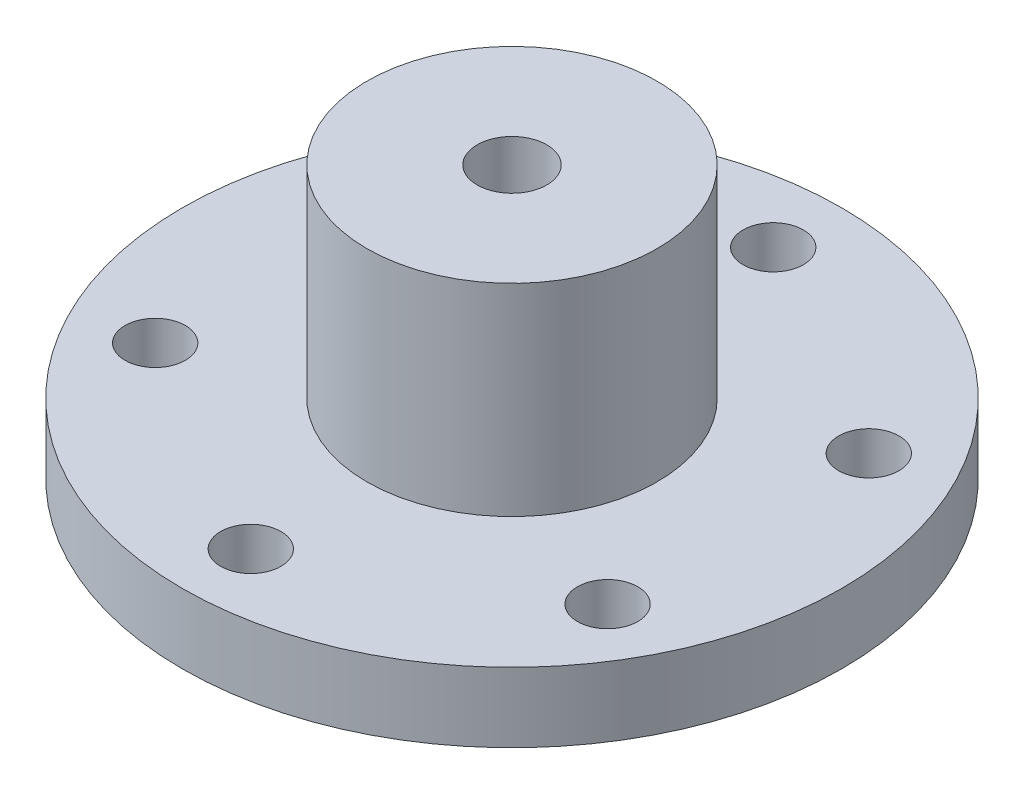
SolidWorks part; units mm, degrees
material "6061 合金"
ref_plane "前视基准面" through (0, 0, 0) normal (0, 0, 1) x (1, 0, 0)
ref_plane "上视基准面" through (0, 0, 0) normal (0, 1, 0) x (1, 0, 0)
ref_plane "右视基准面" through (0, 0, 0) normal (1, 0, 0) x (0, 0, -1)
other "Configuration Table"
sketch "草图1" plane through (0, 0, 0) normal (0, 1, 0) x (1, 0, 0)
  circle A0 centre (0, 0) radius 28.4
extrude "凸台-拉伸1" add sketch "草图1" along normal blind 6
sketch "草图2" plane through (0, 6, 0) normal (0, 1, 0) x (1, 0, 0)
  circle A0 centre (0, 0) radius 12.5
extrude "凸台-拉伸2" add sketch "草图2" along normal blind 17.4
sketch "草图3" plane through (0, 23.4, 0) normal (0, 1, 0) x (1, 0, 0)
  circle A0 centre (0, 0) radius 3
extrude "切除-拉伸1" cut sketch "草图3" against normal blind 60
sketch "草图4" plane through (0, 0, 0) normal (0, -1, 0) x (1, 0, 0)
  line L0 (0, 0) -> (0, 28.4)
  circle A0 centre (0, 0) radius 28.4 construction
  circle A1 centre (0, 0) radius 22.5
  circle A2 centre (0, 22.5) radius 2.6
  circle A3 centre (19.4856, 11.25) radius 2.6
  circle A4 centre (19.4856, -11.25) radius 2.6
  circle A5 centre (0, -22.5) radius 2.6
  circle A6 centre (-19.4856, -11.25) radius 2.6
  circle A7 centre (-19.4856, 11.25) radius 2.6
  point P22 (0, 0)
  dimension "D1" = 6
extrude "切除-拉伸2" cut sketch "草图4" against normal blind 10 contours L0 A2 A1 | A1 A2 L0 | L0 A2 A1 | A1 A2 L0 | A1 A3 | A1 A3 | A1 A4 | A1 A4 | A1 A5 | A1 A5 | A1 A6 | A1 A6 | A1 A7 | A1 A7
